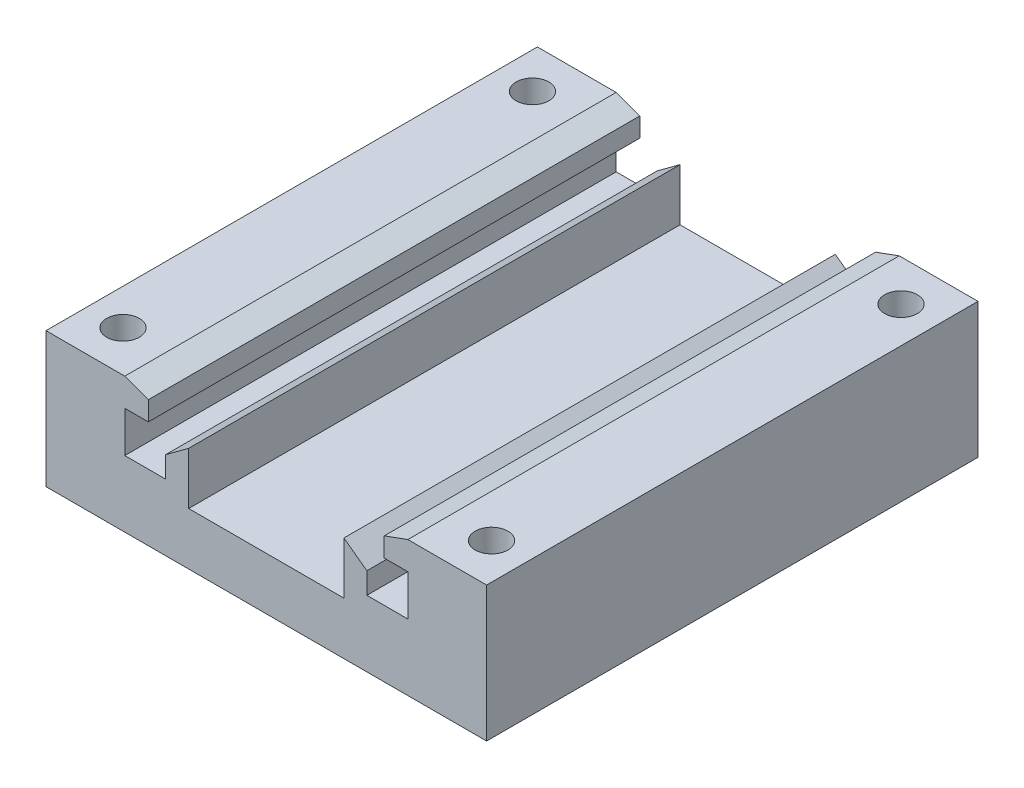
SolidWorks part; units mm, degrees
ref_plane "Front Plane" through (0, 0, 0) normal (0, 0, 1) x (1, 0, 0)
ref_plane "Top Plane" through (0, 0, 0) normal (0, 1, 0) x (1, 0, 0)
ref_plane "Right Plane" through (0, 0, 0) normal (1, 0, 0) x (0, 0, -1)
sketch "Sketch2" plane through (0, 0, 0) normal (0, 0, 1) x (1, 0, 0)
  line L0 (9.62, 16.5) -> (44.18, 16.5)
  line L1 (0, 0) -> (53.8, 0)
  line L2 (0, 0) -> (0, 16.5)
  line L3 (0, 16.5) -> (53.8, 16.5)
  line L4 (53.8, 0) -> (53.8, 16.5)
  line L5 (44.18, 16.5) -> (44.18, 13.1)
  line L6 (36.38, 6.4) -> (36.38, 12.7666)
  line L7 (44.18, 13.1) -> (39.18, 13.1)
  line L8 (44.18, 13.1) -> (44.18, 8.1)
  line L9 (44.18, 8.1) -> (39.18, 8.1)
  line L10 (39.18, 13.1) -> (39.18, 8.1)
  line L11 (53.8, 16.5) -> (41.3, 16.5)
  line L12 (36.38, 16.5) -> (13.5778, 16.5)
  line L13 (36.38, 16.5) -> (36.38, 6.4)
  line L14 (36.38, 6.4) -> (13.5778, 6.4)
  line L15 (13.5778, 16.5) -> (13.5778, 6.4)
  line L16 (41.3, 16.5) -> (41.3, 13.1)
  line L17 (44.18, 16.5) -> (41.3, 15.4518)
  line L18 (39.18, 8.1) -> (39.18, 10.7)
  line L19 (39.18, 10.7) -> (36.38, 12.7666)
  line L20 (53.8, 0) -> (26.9, 0)
  line L21 (26.9, 0) -> (26.9, 16.5)
  line L22 (39.18, 10.7) -> (36.38, 10.7)
  line L23 (36.38, 12.7666) -> (36.38, 10.7)
  point P11 (44.18, 10.6)
  dimension "D1" = 53.8
  dimension "D2" = 16.5
  dimension "D3" = 34.56
  dimension "D4" = 9.62
  dimension "D5" = 3.4
  dimension "D6" = 5
  dimension "D7" = 5
  dimension "D8" = 2.8
  dimension "D9" = 10.1
  dimension "D10" = 12.5
  dimension "D11" = 20
  dimension "D12" = 36.43
  dimension "D13" = 2.6
extrude "Boss-Extrude1" add sketch "Sketch2" against normal blind 60 contours L21 L1 L4 L3 L5 L8 L9 L10 L19 L6 L14 | L5 L17 L16 L7 | L22 L19 L13
mirror "Mirror1" about plane through (26.9, 0, -60) normal (1, 0, 0) of "Boss-Extrude1"
ref_plane "Plane1" through (0, 0, -30) normal (0, 0, 1) x (1, 0, 0)
sketch "Sketch3" plane through (0, 0, 0) normal (0, -1, 0) x (1, 0, 0)
  line L1 (0, -60) -> (0, 0) construction
  line L2 (0, 0) -> (53.8, 0) construction
  line L3 (53.8, -60) -> (53.8, 0) construction
  line L4 (0, -60) -> (53.8, -60) construction
  point P2 (4.4, -5)
  point P5 (49.4, -5)
  point P8 (4.4, -55)
  point P11 (49.4, -55)
  point P12 (67.1619, -19.609)
  dimension "D1" = 4.4
  dimension "D2" = 5
  dimension "D3" = 5
  dimension "D4" = 4.4
  dimension "D5" = 4.4
  dimension "D6" = 5
hole_wizard "Ø4.0mm Dowel Hole1" positions "Sketch4" profile "Sketch5" hole size "Ø4.0" standard "ANSI Metric" end condition through all
sketch "Sketch4" plane through (0, 0, 0) normal (0, -1, 0) x (-1, 0, 0)
  point P0 (-49.4, 55)
  point P3 (-4.4, 55)
  point P6 (-4.4, 5)
  point P9 (-49.4, 5)
sketch "Sketch5" plane through (49.4, 0, -55) normal (1, 0, 0) x (0, 0, -1)
  line L0 (0, 0) -> (0, 16.5)
  line L1 (0, 16.5) -> (2, 16.5)
  line L2 (2, 16.5) -> (2, 0.025)
  line L3 (2, 0.025) -> (2.025, 0)
  line L5 (2.025, 0) -> (0, 0)
  line L6 (-2, 0.025) -> (-2.025, 0) construction
  line L11 (0, -6.35) -> (0, 107.95) construction
  dimension "Thru Hole Dia." = 4
  dimension "Thru Hole Depth" = 16.5
  dimension "Near C'Sink Dia." = 4.05
  dimension "Near C'Sink Angle" = 90
